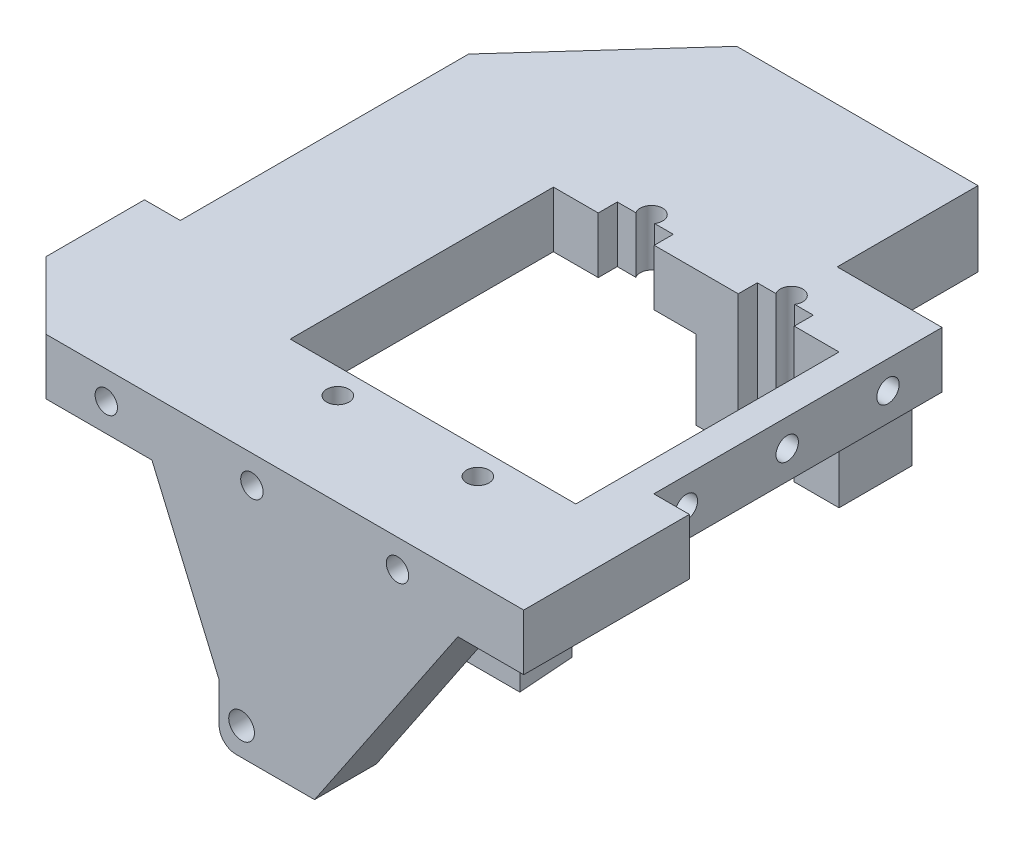
SolidWorks part; units mm, degrees
other "标注1"
sketch "草图3" plane through (-22.95, 0.6154, -67.3001) normal (-0.986, 0.1497, -0.0737) x (0.006, 0.4732, 0.8809)
ref_plane "前视基准面" through (0, 0, 0) normal (0, 0, 1) x (1, 0, 0)
ref_plane "上视基准面" through (0, 0, 0) normal (0, 1, 0) x (1, 0, 0)
ref_plane "右视基准面" through (0, 0, 0) normal (1, 0, 0) x (0, 0, -1)
other "图形1"
other "图形 (闭合) -1"
sketch "草图2" plane through (0, 0, 0) normal (0, 1, 0) x (1, 0, 0)
  line L0 (-16.95, 14.2011) -> (25.7, 14.2011)
  line L1 (25.7, 14.2011) -> (25.7, 28.9928)
  line L2 (25.7, 28.9928) -> (22.524, 28.9928)
  line L3 (22.524, 28.9928) -> (22.524, 54.731)
  line L4 (22.524, 54.731) -> (13.1611, 54.7309)
  line L5 (13.1611, 54.7309) -> (13.1611, 67.3)
  line L6 (13.1611, 67.3) -> (-8.376, 67.3)
  line L7 (-8.376, 67.3) -> (-19.75, 54.731)
  line L8 (-19.75, 54.731) -> (-19.75, 28.9928)
  line L9 (-19.75, 28.9928) -> (-22.95, 28.9928)
  line L10 (-22.95, 28.9928) -> (-22.95, 20.2011)
  line L11 (-22.95, 20.2011) -> (-16.95, 14.2011)
extrude "凸台-拉伸1" add sketch "草图2" along normal blind 5
sketch "草图4" plane through (0, 0, 0) normal (0, -1, 0) x (1, 0, 0)
  line L0 (-5.676, -24.7314) -> (19.824, -24.7314)
  line L1 (19.824, -24.7314) -> (19.824, -48.2314)
  line L2 (19.824, -48.2314) -> (15.824, -48.2314)
  line L3 (15.824, -48.2314) -> (15.824, -49.9314)
  line L4 (15.824, -49.9314) -> (10.824, -49.9314)
  line L5 (10.824, -49.9314) -> (10.824, -48.2314)
  line L6 (10.824, -48.2314) -> (3.324, -48.2314)
  line L7 (3.324, -48.2314) -> (3.324, -49.9314)
  line L8 (3.324, -49.9314) -> (-1.676, -49.9314)
  line L9 (-1.676, -49.9314) -> (-1.676, -48.2314)
  line L10 (-1.676, -48.2314) -> (-5.676, -48.2314)
  line L11 (-5.676, -48.2314) -> (-5.676, -24.7314)
  circle A0 centre (0.824, -22.4814) radius 1
  circle A1 centre (13.324, -22.4814) radius 1
extrude "切除-拉伸1" cut sketch "草图4" against normal blind 5
sketch "草图6" plane through (0, 0, 0) normal (0, -1, 0) x (1, 0, 0)
  circle A0 centre (0.824, -50.4814) radius 1
  circle A1 centre (13.324, -50.4814) radius 1
extrude "切除-拉伸2" cut sketch "草图6" against normal blind 5
sketch "草图7" plane through (0, 5, 0) normal (0, 1, 0) x (1, 0, 0)
  line L0 (15.824, 48.2314) -> (19.824, 48.2314) construction
  line L1 (19.324, 48.2314) -> (7.324, 48.2314) construction
  line L2 (19.324, 48.2314) -> (19.324, 52.7314)
  line L3 (19.324, 52.7314) -> (7.324, 52.7314)
  line L4 (7.324, 48.2314) -> (7.324, 52.7314)
  line L5 (15.824, 48.2314) -> (15.824, 49.9314)
  line L6 (15.824, 49.9314) -> (14.1591, 49.9314)
  line L8 (15.824, 48.2314) -> (19.324, 48.2314)
  line L9 (10.824, 48.2314) -> (7.324, 48.2314)
  line L10 (10.824, 49.9314) -> (10.824, 48.2314)
  line L11 (10.824, 49.9314) -> (12.4888, 49.9314)
  line L12 (19.824, 24.7314) -> (19.824, 48.2314) construction
  line L13 (19.824, 36.4814) -> (18.2439, 36.4814) construction
  line L14 (15.824, 24.7314) -> (19.324, 24.7314)
  line L15 (19.324, 24.7314) -> (19.324, 20.2314)
  line L16 (7.324, 24.7314) -> (7.324, 20.2314)
  line L17 (19.324, 20.2314) -> (7.324, 20.2314)
  line L18 (15.824, 24.7314) -> (7.324, 24.7314)
  arc A0 (14.1591, 49.9314) -> (12.4888, 49.9314) centre (13.324, 50.4814) ccw
  arc A1 (14.1591, 23.0314) -> (12.4888, 23.0314) centre (13.324, 22.4814) cw
  arc A2 (12.4888, 23.0314) -> (14.1591, 23.0314) centre (13.324, 22.4814) cw
  dimension "D1" = 3.5
  dimension "D2" = 3.5
  dimension "D3" = 4.5
extrude "凸台-拉伸2" [suppressed] add sketch "草图7" along normal blind 7.05
sketch "草图8" plane through (0, 0, 0) normal (0, 0, 1) x (1, 0, 0)
  line L0 (-2.0062, -4.385) -> (-8.0062, -18.385)
  line L1 (19.3117, -18.385) -> (6.5117, 0.615)
  line L2 (-0.5062, 0.615) -> (6.5117, 0.615)
  line L3 (-2.0062, -4.385) -> (-2.0062, -0.885)
  line L4 (-8.0062, -18.385) -> (19.3117, -18.385)
  circle A0 centre (0, -1.85) radius 1.15
  arc A1 (-0.5062, 0.615) -> (-2.0062, -0.885) centre (-0.5062, -0.885) ccw
  dimension "D1" = 1.5
sketch "草图10" [suppressed] plane through (0, 0, -20.2314) normal (0, 0, 1) x (1, 0, 0)
  line L0 (-1.994, 19) -> (-7.994, 5)
  line L1 (19.324, 5) -> (6.524, 24)
  line L2 (-0.494, 24) -> (6.524, 24)
  line L3 (-1.994, 19) -> (-1.994, 22.5)
  line L4 (-7.994, 5) -> (19.324, 5)
  circle A0 centre (0.0122, 21.5351) radius 1.15
  arc A1 (-0.494, 24) -> (-1.994, 22.5) centre (-0.494, 22.5) ccw
  dimension "D1" = 1.5
extrude "凸台-拉伸3" [suppressed] add sketch "草图10" along normal blind 6
sketch "草图11" plane through (0, 5, 0) normal (0, 1, 0) x (1, 0, 0)
  line L0 (13.1611, 67.3) -> (13.1611, 54.7309)
  line L1 (13.1611, 67.3) -> (-8.376, 67.3)
  line L2 (-8.376, 67.3) -> (-8.6014, 54.7309)
  line L3 (-8.6014, 54.7309) -> (13.1611, 54.7309)
extrude "凸台-拉伸4" [suppressed] add sketch "草图11" along normal blind 1.68
sketch "草图12" plane through (0, 0, 0) normal (0, 0, 1) x (1, 0, 0)
  line L0 (-16.95, -18.385) -> (-16.95, -23.385)
  circle A0 centre (1.432, -20.885) radius 1
  circle A1 centre (14.432, -20.8846) radius 1
  circle A2 centre (-11.568, -20.8846) radius 1
sketch "草图13" plane through (0, 0, -14.2011) normal (0, 0, 1) x (1, 0, 0)
  line L0 (-16.95, 5) -> (-16.95, 0) construction
  circle A0 centre (1.432, 2.5) radius 1
  circle A1 centre (14.432, 2.5004) radius 1
  circle A2 centre (-11.568, 2.5004) radius 1
extrude "切除-拉伸3" cut sketch "草图13" against normal blind 6
sketch "草图14" plane through (0, 0, 0) normal (0, 0, 1) x (1, 0, 0)
  line L0 (13.1611, -23.3822) -> (13.1611, -22.4695)
  circle A0 centre (8.1994, -20.0406) radius 1
  circle A1 centre (-2.8006, -20.0406) radius 1
sketch "草图16" plane through (0, 0, -67.3) normal (0, 0, -1) x (-1, 0, 0)
  line L0 (8.4404, 0) -> (8.4404, 0.9127) construction
  line L1 (-8.1611, 3.3415) -> (2.8389, 3.3415) construction
  line L2 (-13.1611, 5) -> (-13.1611, 0) construction
  circle A0 centre (2.8389, 3.3415) radius 1
  circle A1 centre (-8.1611, 3.3415) radius 1
  dimension "D1" = 11
  dimension "D2" = 5
extrude "切除-拉伸4" [suppressed] cut sketch "草图16" against normal blind 8
sketch "草图17" plane through (0, 0, 0) normal (1, 0, 0) x (0, 0, -1)
  line L0 (54.7314, -23.3822) -> (54.7314, -22.1204)
  circle A0 centre (31.9019, -20.8669) radius 1
  circle A1 centre (40.9018, -20.824) radius 1
  circle A2 centre (49.9017, -20.8669) radius 1
sketch "草图18" plane through (22.524, 0, 0) normal (1, 0, 0) x (0, 0, -1)
  circle A0 centre (31.9015, 2.5152) radius 1
  circle A1 centre (40.9014, 2.5581) radius 1
  circle A2 centre (49.9013, 2.5152) radius 1
extrude "切除-拉伸5" cut sketch "草图18" against normal blind 3.5
sketch "草图19" plane through (0, 0, 0) normal (1, 0, 0) x (0, 0, -1)
  line L0 (67.3001, -23.3813) -> (67.3001, -20.1412)
  circle A0 centre (61.1387, -19.25) radius 1
sketch "草图20" plane through (13.1611, 0, 0) normal (1, 0, 0) x (0, 0, -1)
  circle A0 centre (61.1386, 4.1313) radius 1
extrude "切除-拉伸6" [suppressed] cut sketch "草图20" against normal up to surface (21.6297 mm away)
sketch "草图21" plane through (0, 0, 0) normal (1, 0, 0) x (0, 0, -1)
  line L0 (54.731, -18.3822) -> (54.731, -19.6279)
  circle A0 centre (49.9017, -20.8669) radius 1
  circle A1 centre (40.9018, -20.824) radius 1
  circle A2 centre (31.9019, -20.8669) radius 1
sketch "草图23" plane through (-19.75, 0, 0) normal (-1, 0, 0) x (0, 0, 1)
  line L1 (-49.901, 2.5) -> (-40.901, 2.5) construction
  line L2 (-40.901, 2.5) -> (-31.901, 2.5) construction
  line L3 (-54.731, 5) -> (-54.731, 0) construction
  line L4 (-54.731, 0) -> (-28.9928, 0) construction
  circle A0 centre (-31.901, 2.5) radius 1
  circle A1 centre (-40.901, 2.5) radius 1
  circle A2 centre (-49.901, 2.5) radius 1
  dimension "D1" = 9
  dimension "D2" = 9
  dimension "D3" = 4.83
  dimension "D4" = 2.5
extrude "切除-拉伸7" cut sketch "草图23" against normal blind 12
sketch "草图26" plane through (0, 0, 0) normal (0, -1, 0) x (1, 0, 0)
  line L0 (7.074, -48.2314) -> (7.074, -54.7309)
  line L1 (3.324, -48.2314) -> (10.824, -48.2314) construction
  line L2 (7.074, -48.2314) -> (10.824, -48.2314)
  line L3 (19.824, -48.2314) -> (19.824, -54.731)
  line L4 (22.524, -54.731) -> (13.1611, -54.7309) construction
  line L5 (19.824, -54.731) -> (7.074, -54.7309)
  line L6 (10.824, -48.2314) -> (10.824, -49.9314)
  line L7 (10.824, -49.9314) -> (12.4888, -49.9314)
  line L8 (14.1591, -49.9314) -> (15.824, -49.9314)
  line L9 (15.824, -49.9314) -> (15.824, -48.2314)
  line L10 (15.824, -48.2314) -> (19.824, -48.2314) construction
  line L11 (15.824, -48.2314) -> (19.824, -48.2314)
  line L12 (6.6583, -24.7314) -> (6.6583, -19.7314)
  line L13 (19.824, -24.7314) -> (-5.676, -24.7314) construction
  line L14 (6.6583, -19.7314) -> (19.824, -19.7314)
  line L15 (19.824, -19.7314) -> (19.4663, -24.7314)
  line L16 (19.4663, -24.7314) -> (6.6583, -24.7314)
  arc A0 (12.4888, -49.9314) -> (14.1591, -49.9314) centre (13.324, -50.4814) ccw
  circle A1 centre (13.324, -22.4814) radius 1
extrude "凸台-拉伸5" add sketch "草图26" along normal blind 7.05 separate body
sketch "草图27" plane through (0, 0, 0) normal (0, -1, 0) x (1, 0, 0)
  line L0 (13.1611, -67.3) -> (13.1611, -54.7309)
  line L1 (13.1611, -67.3) -> (-8.376, -67.3)
  line L2 (-8.376, -67.3) -> (-8.376, -54.7309)
  line L3 (-8.376, -54.7309) -> (13.1611, -54.7309)
extrude "凸台-拉伸6" add sketch "草图27" along normal blind 1.68
sketch "草图28" plane through (0, 0, -67.3) normal (0, 0, -1) x (-1, 0, 0)
  line L0 (-8.1611, 1.66) -> (2.8389, 1.66) construction
  line L1 (-8.1611, 1.66) -> (-13.1611, 1.66) construction
  line L2 (-13.1611, 5) -> (-13.1611, -1.68) construction
  line L3 (-13.1611, 5) -> (8.376, 5) construction
  circle A0 centre (-8.1611, 1.66) radius 1
  circle A1 centre (2.8389, 1.66) radius 1
  dimension "D1" = 3.34
extrude "切除-拉伸8" cut sketch "草图28" against normal blind 8
sketch "草图29" plane through (0, 0, -19.7314) normal (0, 0, 1) x (1, 0, 0)
  line L4 (-7.494, 0) -> (19.824, 0)
  line L5 (-1.494, -14) -> (-1.494, -17.5)
  line L6 (0.006, -19) -> (7.024, -19)
  line L7 (19.824, 0) -> (7.024, -19)
  line L8 (-1.494, -14) -> (-7.494, 0)
  arc A2 (0.006, -19) -> (-1.494, -17.5) centre (0.006, -17.5) cw
  circle A3 centre (0.5122, -16.5351) radius 1.15
extrude "凸台-拉伸7" add sketch "草图29" along normal up to surface (5.5303 mm away) up to face at (-10.568, 2.5004, -14.2011)
